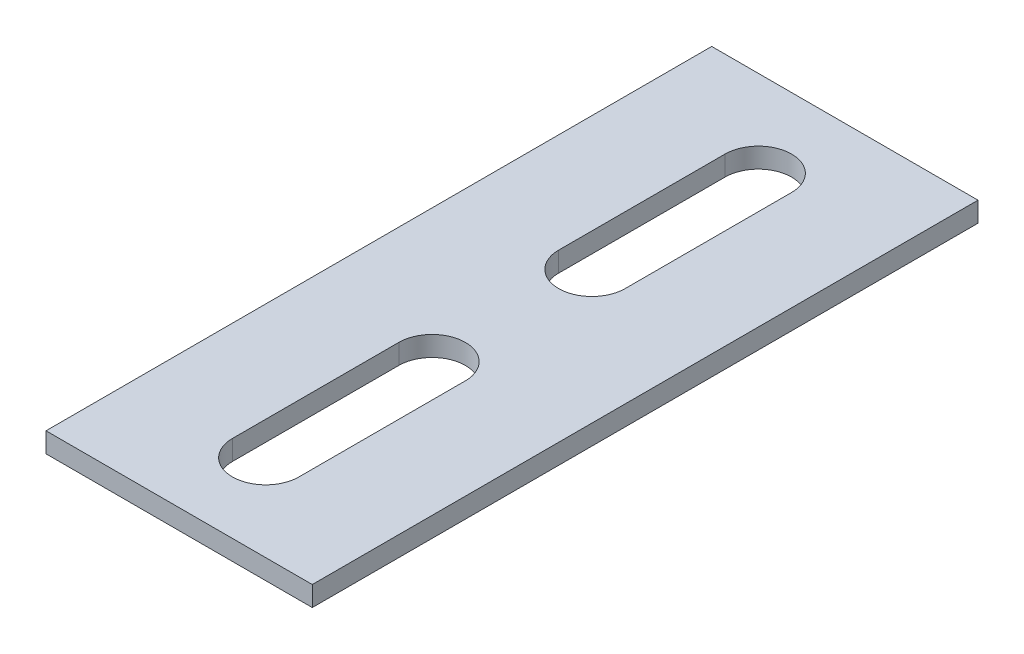
SolidWorks part; units mm, degrees
material "Оцинкованная сталь"
ref_plane "Спереди" through (0, 0, 0) normal (0, 0, 1) x (1, 0, 0)
ref_plane "Сверху" through (0, 0, 0) normal (0, 1, 0) x (1, 0, 0)
ref_plane "Справа" through (0, 0, 0) normal (1, 0, 0) x (0, 0, -1)
sketch "Эскиз2" plane through (0, 0, 0) normal (0, 1, 0) x (1, 0, 0)
  line L0 (0, 12) -> (0, 37) construction
  line L1 (-20, -50) -> (20, -50)
  line L2 (-20, -50) -> (-20, 50)
  line L3 (-20, 50) -> (20, 50)
  line L4 (20, -50) -> (20, 50)
  line L5 (0, 50) -> (0, -50) construction
  line L6 (-20, 0) -> (20, 0) construction
  line L7 (-5, 12) -> (-5, 37)
  line L8 (5, 12) -> (5, 37)
  line L9 (0, -37) -> (0, -12) construction
  line L10 (-5, -37) -> (-5, -12)
  line L11 (5, -37) -> (5, -12)
  arc A0 (-5, 12) -> (5, 12) centre (0, 12) ccw
  arc A1 (5, 37) -> (-5, 37) centre (0, 37) ccw
  arc A2 (-5, -37) -> (5, -37) centre (0, -37) ccw
  arc A3 (5, -12) -> (-5, -12) centre (0, -12) ccw
  point P0 (0, 0)
  point P6 (0, 24.5)
  point P13 (0, -24.5)
  dimension "D12" = 14
  dimension "D14" = 5
  dimension "D15" = 35
  dimension "D16" = 8
  dimension "D1" = 100
  dimension "D2" = 40
  dimension "D3" = 10
  dimension "D4" = 8
  dimension "D5" = 13
  dimension "D6" = 25
  dimension "D7" = 15
  dimension "D8" = 15
  dimension "D9" = 20
  dimension "D10" = 20
  dimension "D11" = 24
  dimension "D13" = 25
extrude "Бобышка-Вытянуть1" add sketch "Эскиз2" along normal mid plane 3
